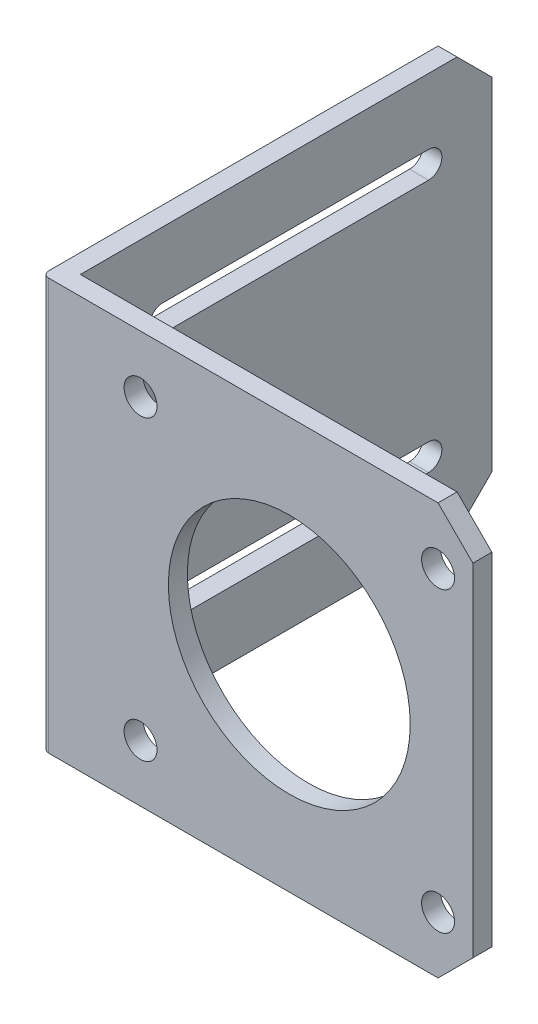
SolidWorks part; units mm, degrees
ref_plane "前视基准面" through (0, 0, 0) normal (0, 0, 1) x (1, 0, 0)
ref_plane "上视基准面" through (0, 0, 0) normal (0, 1, 0) x (1, 0, 0)
ref_plane "右视基准面" through (0, 0, 0) normal (1, 0, 0) x (0, 0, -1)
other "Configuration Table"
sketch "草图1" plane through (0, 0, 0) normal (1, 0, 0) x (0, 0, -1)
  line L1 (34, -32.5) -> (-34, -32.5)
  line L2 (34, -32.5) -> (34, 32.5)
  line L3 (34, 32.5) -> (-34, 32.5)
  line L4 (-34, -32.5) -> (-34, 32.5)
  line L5 (34, -32.5) -> (-34, 32.5) construction
  line L6 (34, 32.5) -> (-34, -32.5) construction
  point P0 (0, 0)
  dimension "D1" = 68
  dimension "D2" = 65
extrude "凸台-拉伸1" add sketch "草图1" along normal blind 68
sketch "草图2" plane through (68, 0, 0) normal (1, 0, 0) x (0, 0, -1)
  line L0 (-31, 32.5) -> (-31, -32.5)
  line L1 (34, 32.5) -> (-34, 32.5) construction
  line L2 (-34, -32.5) -> (34, -32.5) construction
  line L3 (-31, -32.5) -> (34, -32.5)
  line L4 (34, -32.5) -> (34, 32.5)
  line L5 (34, 32.5) -> (-31, 32.5)
  line L6 (-34, 32.5) -> (-34, -32.5) construction
  dimension "D1" = 3
extrude "切除-拉伸1" cut sketch "草图2" against normal blind 65
fillet "圆角1" radius 1 1 edges at (0, 0, 34)
ref_plane "基准面1" through (0, 0, 0) normal (0, 1, 0) x (1, 0, 0)
sketch "草图6" plane through (0, 0, 31) normal (0, 0, -1) x (-1, 0, 0)
  line L1 (-68, 32.5) -> (-68, -32.5) construction
  line L3 (-3, 32.5) -> (-68, 32.5) construction
  line L4 (37.4, 0) -> (-37.4, 0) construction
  line L5 (-68, 32.5) -> (-68, 27)
  line L6 (-68, 27) -> (-62.5, 32.5)
  line L7 (-62.5, 32.5) -> (-68, 32.5)
  line L8 (-68, -27) -> (-62.5, -32.5)
  line L9 (-68, -32.5) -> (-68, -27)
  line L10 (-62.5, -32.5) -> (-68, -32.5)
  circle A0 centre (-62.5, 23.5) radius 2.6
  circle A1 centre (-15.5, 23.5) radius 2.6
  circle A2 centre (-39, 0) radius 19.1
  circle A3 centre (-15.5, -23.5) radius 2.6
  circle A4 centre (-62.5, -23.5) radius 2.6
  dimension "D1" = 5.2
  dimension "D2" = 5.2
  dimension "D3" = 47
  dimension "D4" = 5.5
  dimension "D5" = 38.2
  dimension "D6" = 32.5
  dimension "D7" = 29
  dimension "D8" = 23.5
  dimension "D9" = 5.5
  dimension "D10" = 5.5
extrude "切除-拉伸4" cut sketch "草图6" against normal blind 51
sketch "草图7" plane through (3, 0, 0) normal (1, 0, 0) x (0, 0, -1)
  line L0 (28.5, 32.5) -> (34, 32.5)
  line L1 (34, 32.5) -> (-31, 32.5) construction
  line L2 (34, 32.5) -> (34, 27)
  line L3 (34, -32.5) -> (34, 32.5) construction
  line L4 (34, 27) -> (28.5, 32.5)
  line L5 (37.4, 0) -> (-37.4, 0) construction
  line L6 (-18, 22.1) -> (24, 22.1)
  line L8 (-18, 17.9) -> (24, 17.9)
  line L10 (34, -32.5) -> (34, -27)
  line L11 (28.5, -32.5) -> (34, -32.5)
  line L12 (34, -27) -> (28.5, -32.5)
  line L13 (-18, -17.9) -> (24, -17.9)
  line L14 (-18, -22.1) -> (24, -22.1)
  arc A0 (-18, 17.9) -> (-18, 22.1) centre (-18, 20) cw
  arc A1 (24, 17.9) -> (24, 22.1) centre (24, 20) ccw
  arc A2 (-18, -17.9) -> (-18, -22.1) centre (-18, -20) ccw
  arc A3 (24, -17.9) -> (24, -22.1) centre (24, -20) cw
  dimension "D6" = 10
  dimension "D1" = 5.5
  dimension "D2" = 5.5
  dimension "D3" = 10.4
  dimension "D4" = 4.2
  dimension "D5" = 42
extrude "切除-拉伸5" cut sketch "草图7" against normal blind 51
